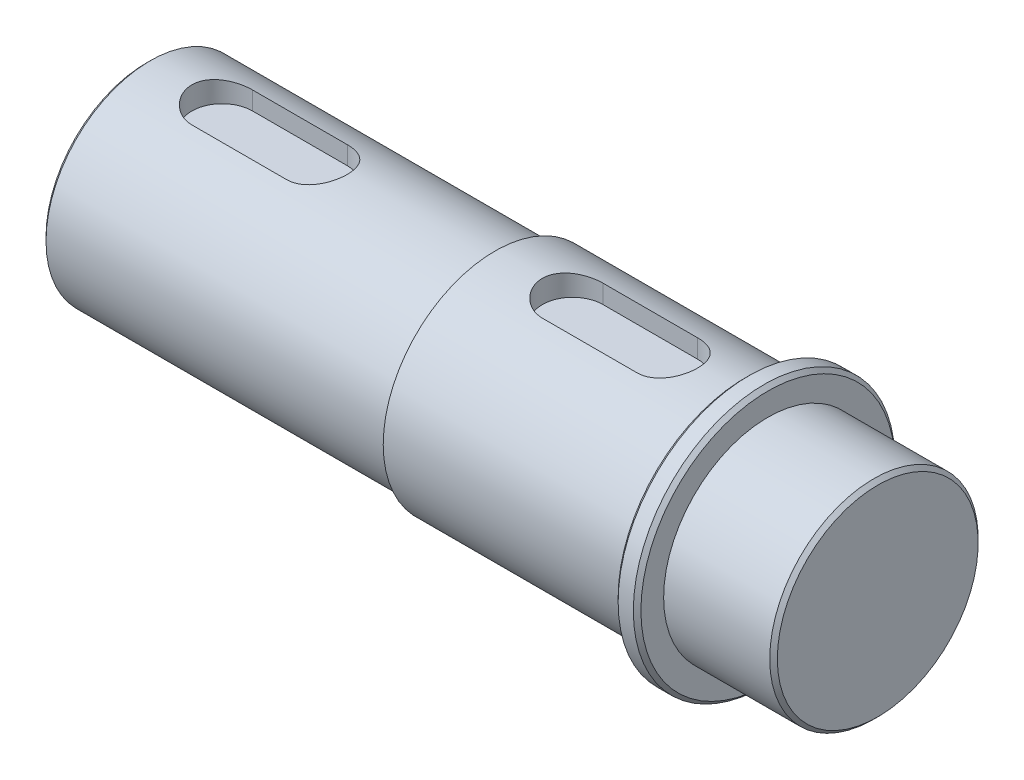
SolidWorks part; units mm, degrees
ref_plane "Front Plane" through (0, 0, 0) normal (0, 0, 1) x (1, 0, 0)
ref_plane "Top Plane" through (0, 0, 0) normal (0, 1, 0) x (1, 0, 0)
ref_plane "Right Plane" through (0, 0, 0) normal (1, 0, 0) x (0, 0, -1)
sketch "Sketch1" plane through (0, 0, 0) normal (0, 0, 1) x (1, 0, 0)
  line L0 (-72.2363, 0) -> (85.0586, 0) construction
  line L1 (-59.6496, 0) -> (-59.6496, 27.5)
  line L2 (-59.6496, 27.5) -> (-30.66, 27.5)
  line L3 (70.34, 26.5) -> (70.34, 0)
  line L4 (35.332, 29.5) -> (35.332, 33.5)
  line L5 (36.332, 34.5) -> (40.34, 34.5)
  line L6 (41.34, 33.5) -> (41.34, 27.5)
  line L7 (35.332, 33.5) -> (36.332, 34.5)
  line L8 (40.34, 34.5) -> (41.34, 33.5)
  line L9 (69.34, 27.5) -> (70.34, 26.5)
  line L11 (-30.66, 27.5) -> (-30.66, 29.5)
  line L12 (-30.66, 29.5) -> (35.332, 29.5)
  line L13 (41.34, 27.5) -> (69.34, 27.5)
  line L14 (-59.6496, 0) -> (70.34, 0)
  point P4 (-59.6496, 27.5)
  point P5 (-30.66, 27.5)
  point P6 (70.34, 27.5)
  point P8 (35.34, 27.5)
  point P9 (17.84, 27.5)
  point P10 (0.34, 27.5)
  point P11 (41.34, 27.5)
  point P12 (-59.66, 26.5)
  point P13 (35.332, 34.5)
  point P15 (41.34, 34.5)
  point P27 (0, 0)
  point P28 (0, 0)
  point P29 (-59.5628, 27.5)
  dimension "D5" = 17.5
  dimension "D6" = 17.5
  dimension "D7" = 29
  dimension "D9" = 2
revolve "Revolve1" add sketch "Sketch1" angle 360 about L0
ref_plane "Plane1" through (0, 29.5, 0) normal (0, 1, 0) x (1, 0, 0)
sketch "Sketch2" plane through (0, 29.5, 0) normal (0, 1, 0) x (1, 0, 0)
  line L3 (-10.168, 0) -> (14.832, 0) construction
  line L4 (-10.168, 8) -> (14.832, 8)
  line L5 (-10.168, -8) -> (14.832, -8)
  arc A0 (-10.168, 8) -> (-10.168, -8) centre (-10.168, 0) ccw
  arc A1 (14.832, -8) -> (14.832, 8) centre (14.832, 0) ccw
  point P8 (2.332, 0)
  dimension "D1" = 25
  dimension "D3" = 16
extrude "Cut-Extrude1" cut sketch "Sketch2" against normal blind 6
sketch "Sketch3" plane through (-59.6496, 0, 0) normal (-1, 0, 0) x (0, 0, 1)
  circle A2 centre (0, 0) radius 27.5
  circle A3 centre (0, 0) radius 27.5
  dimension "D1" = 0
extrude "Boss-Extrude1" add sketch "Sketch3" along normal blind 63
chamfer "Chamfer1" distance 1 angle 45 1 edges at (-122.6496, 0, 27.5)
ref_plane "Plane2" through (0, 27.5, 0) normal (0, 1, 0) x (1, 0, 0)
sketch "Sketch4" plane through (0, 27.5, 0) normal (0, 1, 0) x (1, 0, 0)
  line L4 (-102.6496, 0) -> (-77.6496, 0) construction
  line L5 (-102.6496, 8) -> (-77.6496, 8)
  line L6 (-102.6496, -8) -> (-77.6496, -8)
  arc A0 (-102.6496, 8) -> (-102.6496, -8) centre (-102.6496, 0) ccw
  arc A1 (-77.6496, -8) -> (-77.6496, 8) centre (-77.6496, 0) ccw
  point P6 (-58.6496, 0)
  point P7 (-90.1496, 0)
  point P13 (0, 0)
  dimension "D1" = 16
  dimension "D2" = 25
extrude "Cut-Extrude2" cut sketch "Sketch4" against normal blind 6
